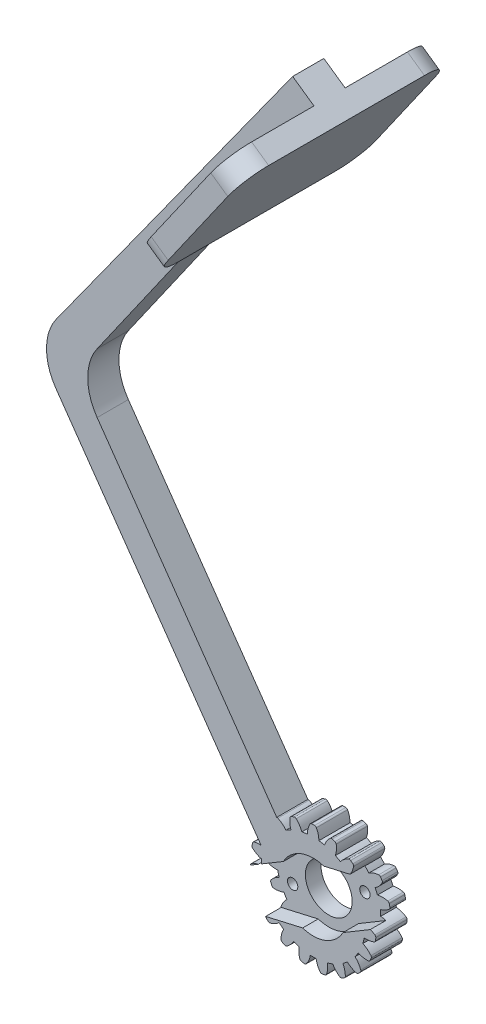
SolidWorks part; units mm, degrees
material "ABS"
ref_plane "Front Plane" through (0, 0, 0) normal (0, 0, 1) x (1, 0, 0)
ref_plane "Top Plane" through (0, 0, 0) normal (0, 1, 0) x (1, 0, 0)
ref_plane "Right Plane" through (0, 0, 0) normal (1, 0, 0) x (0, 0, -1)
sketch "Sketch1" plane through (0, 0, 0) normal (0, 0, 1) x (1, 0, 0)
  line L0 (0, 0) -> (0, 12.075) construction
  arc A0 (-1.1, 9.9393) -> (1.1, 9.9393) centre (0, 0) ccw
  arc A1 (0.2764, 12.0718) -> (-0.2764, 12.0718) centre (0, 0) ccw
  arc A2 (0.6177, 11.8646) -> (0.2764, 12.0718) centre (0.2672, 11.6719) ccw
  arc A3 (-0.6177, 11.8646) -> (-0.2764, 12.0718) centre (-0.2672, 11.6719) cw
  arc A4 (0, 10) -> (-1.1, 9.9393) centre (0, 0) ccw construction
  arc A5 (1.1, 9.9393) -> (0, 10) centre (0, 0) ccw construction
  circle A21 centre (0, 0) radius 1.5
  spline S0 degree 3 poles (-0.6177, 11.8646) (-0.9346, 11.2883) (-1.1207, 10.6005) (-1.1, 9.9393) knots 0.104246 0.104246 0.104246 0.104246 1 1 1 1
  spline S1 degree 3 poles (0.6177, 11.8646) (0.9636, 11.2354) (1.0591, 10.6328) (1.1, 9.9393) knots 0.104246 0.104246 0.104246 0.104246 1 1 1 1
  point P127 (0, 0)
  dimension "D1" = 20
  dimension "D2" = 24.15
  dimension "D7" = 0.4
  dimension "D3" = 3
  dimension "D8" = 0.5527
  dimension "D16" = 1.2197
  dimension "D17" = 1.0456
  dimension "D4" = 1
  dimension "D5" = 1.1
  dimension "D6" = 1.2
  dimension "D9" = 0.2672
  dimension "D10" = 1.1
  dimension "D11" = 0.6177
  dimension "D12" = 1
  dimension "D13" = 1.1
  dimension "D14" = 0.6177
  dimension "D15" = 10.8
extrude "Boss-Extrude1" add sketch "Sketch1" along normal blind 6
pattern_circular "CirPattern1" count 19 over 360 about axis through (0, 0, 6) along (0, 0, -1) of "Boss-Extrude1"
sketch "Sketch2" plane through (0, 0, 6) normal (0, 0, 1) x (1, 0, 0)
  line L7 (-7.5, 0) -> (7.5, 0) construction
  line L12 (-2.5851, 3.4415) -> (-41.5871, 59.1421)
  line L13 (-41.5871, 70.6136) -> (0.9678, 131.3883)
  line L14 (0.9678, 131.3883) -> (-3.9471, 134.8298)
  line L15 (-3.9471, 134.8298) -> (-49.4558, 71.6045)
  line L16 (-49.5312, 60.0268) -> (-7.5, 0)
  line L17 (-7.5, 0) -> (-2.5851, 3.4415)
  arc A0 (-41.5871, 59.1421) -> (-41.5871, 70.6136) centre (-33.3956, 64.8779) cw
  arc A1 (-49.4558, 71.6045) -> (-49.5312, 60.0268) centre (-41.3397, 65.7625) ccw
  point P9 (-45.6033, 64.8779)
  point P13 (0, 0)
  point P15 (-53.6033, 65.8424)
  dimension "D9" = 10
  dimension "D1" = 15
  dimension "D2" = 6
  dimension "D3" = 75
  dimension "D4" = 6
  dimension "D5" = 110
  dimension "D6" = 35
  dimension "D7" = 85
  dimension "D8" = 8
extrude "Boss-Extrude2" add sketch "Sketch2" against normal blind 6
sketch "Sketch4" plane through (0, 0, 6) normal (0, 0, 1) x (1, 0, 0)
  line L0 (5.7373, -3.0551) -> (16.8492, 3.5671)
  line L5 (14.6421, 9.0681) -> (2.0345, 6.1734)
  line L6 (-5.7373, 3.0551) -> (-16.8492, -3.5671)
  line L7 (-14.6421, -9.0681) -> (-2.0345, -6.1734)
  line L10 (5.3589, -2.6986) -> (16.5932, 3.9966)
  line L11 (14.7539, 8.5807) -> (2.0075, 5.6542)
  line L12 (-5.3589, 2.6986) -> (-16.5932, -3.9966)
  line L13 (-14.7539, -8.5807) -> (-2.0075, -5.6542)
  line L14 (5.3589, -2.6986) -> (16.5932, 3.9966) construction
  line L15 (14.7539, 8.5807) -> (2.0075, 5.6542) construction
  line L16 (-5.3589, 2.6986) -> (-16.5932, -3.9966) construction
  line L17 (-14.7539, -8.5807) -> (-2.0075, -5.6542) construction
  arc A2 (16.8492, 3.5671) -> (14.6421, 9.0681) centre (15.3134, 6.1441) ccw
  arc A3 (2.0345, 6.1734) -> (-5.7373, 3.0551) centre (0, 0) ccw
  arc A4 (-16.8492, -3.5671) -> (-14.6421, -9.0681) centre (-15.3134, -6.1441) ccw
  arc A5 (-2.0345, -6.1734) -> (5.7373, -3.0551) centre (0, 0) ccw
  arc A6 (-2.0075, -5.6542) -> (5.3589, -2.6986) centre (0, 0) ccw
  arc A7 (16.5932, 3.9966) -> (14.7539, 8.5807) centre (15.3134, 6.1441) ccw
  arc A8 (2.0075, 5.6542) -> (-5.3589, 2.6986) centre (0, 0) ccw
  arc A9 (-16.5932, -3.9966) -> (-14.7539, -8.5807) centre (-15.3134, -6.1441) ccw
  arc A10 (-2.0075, -5.6542) -> (5.3589, -2.6986) centre (0, 0) ccw construction
  arc A11 (16.5932, 3.9966) -> (14.7539, 8.5807) centre (15.3134, 6.1441) ccw construction
  arc A12 (2.0075, 5.6542) -> (-5.3589, 2.6986) centre (0, 0) ccw construction
  arc A13 (-16.5932, -3.9966) -> (-14.7539, -8.5807) centre (-15.3134, -6.1441) ccw construction
  dimension "D1" = 0.5
  dimension "D4" = 0
extrude "Cut-Extrude1" cut sketch "Sketch4" against normal blind 3
sketch "Sketch5" plane through (0, 0, 0) normal (0, 0, -1) x (-1, 0, 0)
  circle A0 centre (0, 0) radius 4.5
  dimension "D1" = 9
extrude "Cut-Extrude2" cut sketch "Sketch5" against normal through all both and the other way through all
sketch "Sketch6" plane through (0, 0, 3) normal (0, 0, 1) x (1, 0, 0)
  circle A0 centre (-6.9606, -2.7928) radius 1
  circle A1 centre (6.9606, 2.7928) radius 1
  dimension "D1" = 2
  dimension "D2" = 2
extrude "Cut-Extrude3" cut sketch "Sketch6" against normal through all both and the other way through all
sketch "Sketch7" plane through (-61.0829, 42.7707, 0) normal (0.8192, -0.5736, 0) x (0, 0, -1)
  line L0 (0, 108.1821) -> (-6, 108.1821) construction
  line L1 (-18, 78.1821) -> (12, 78.1821)
  line L2 (-23, 83.1821) -> (-23, 103.1821)
  line L3 (-18, 108.1821) -> (12, 108.1821)
  line L4 (17, 83.1821) -> (17, 103.1821)
  arc A0 (12, 108.1821) -> (17, 103.1821) centre (12, 103.1821) cw
  arc A1 (12, 78.1821) -> (17, 83.1821) centre (12, 83.1821) ccw
  arc A2 (-18, 78.1821) -> (-23, 83.1821) centre (-18, 83.1821) cw
  arc A3 (-23, 103.1821) -> (-18, 108.1821) centre (-18, 103.1821) cw
  point P6 (-3, 108.1821)
  point P7 (-3, 108.1821)
  point P10 (17, 108.1821)
  point P15 (-23, 78.1821)
  point P18 (-23, 108.1821)
  dimension "D3" = 5
  dimension "D1" = 40
  dimension "D2" = 30
extrude "Boss-Extrude3" add sketch "Sketch7" along normal blind 3 and the other way blind 1
